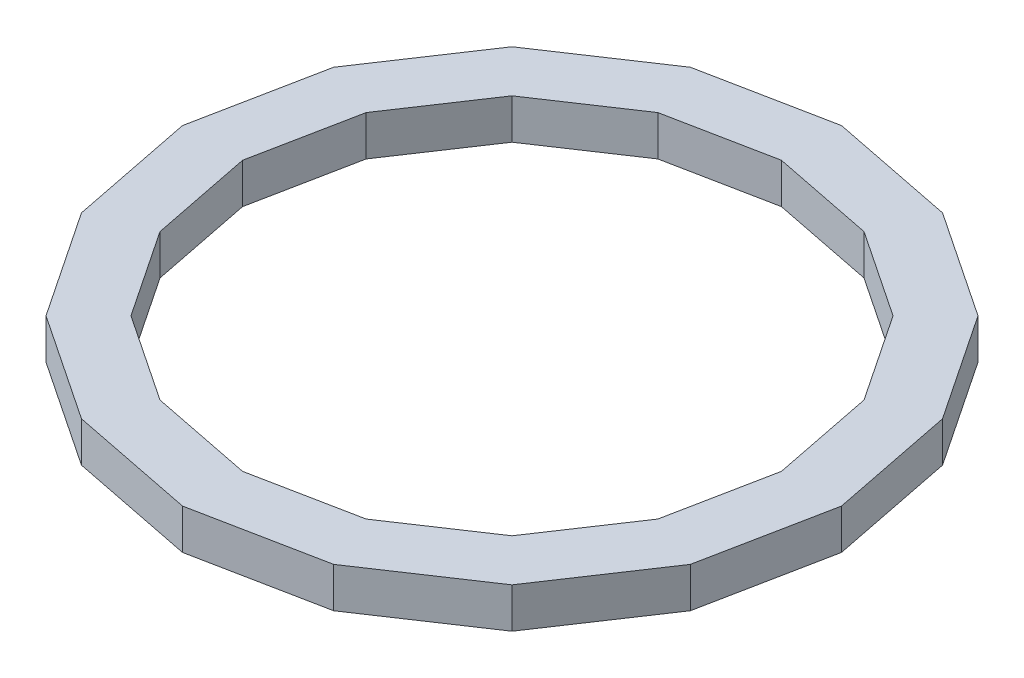
SolidWorks part; units mm, degrees
ref_plane "Front Plane" through (0, 0, 0) normal (0, 0, 1) x (1, 0, 0)
ref_plane "Top Plane" through (0, 0, 0) normal (0, 1, 0) x (1, 0, 0)
ref_plane "Right Plane" through (0, 0, 0) normal (1, 0, 0) x (0, 0, -1)
sketch "Sketch1" plane through (0, 0, 0) normal (0, 1, 0) x (1, 0, 0)
  line L1 (156.2353, 0) -> (144.3426, 59.7887)
  line L2 (144.3426, 59.7887) -> (110.4751, 110.4751)
  line L3 (110.4751, 110.4751) -> (59.7887, 144.3426)
  line L4 (59.7887, 144.3426) -> (0, 156.2353)
  line L5 (0, 156.2353) -> (-59.7887, 144.3426)
  line L6 (-59.7887, 144.3426) -> (-110.4751, 110.4751)
  line L7 (-110.4751, 110.4751) -> (-144.3426, 59.7887)
  line L8 (-144.3426, 59.7887) -> (-156.2353, 0)
  line L9 (-156.2353, 0) -> (-144.3426, -59.7887)
  line L10 (-144.3426, -59.7887) -> (-110.4751, -110.4751)
  line L11 (-110.4751, -110.4751) -> (-59.7887, -144.3426)
  line L12 (-59.7887, -144.3426) -> (0, -156.2353)
  line L13 (0, -156.2353) -> (59.7887, -144.3426)
  line L14 (59.7887, -144.3426) -> (110.4751, -110.4751)
  line L15 (110.4751, -110.4751) -> (144.3426, -59.7887)
  line L16 (144.3426, -59.7887) -> (156.2353, 0)
  line L17 (127.7479, 0) -> (118.0237, 48.887)
  line L18 (118.0237, 48.887) -> (90.3314, 90.3314)
  line L19 (90.3314, 90.3314) -> (48.887, 118.0237)
  line L20 (48.887, 118.0237) -> (0, 127.7479)
  line L21 (0, 127.7479) -> (-48.887, 118.0237)
  line L22 (-48.887, 118.0237) -> (-90.3314, 90.3314)
  line L23 (-90.3314, 90.3314) -> (-118.0237, 48.887)
  line L24 (-118.0237, 48.887) -> (-127.7479, 0)
  line L25 (-127.7479, 0) -> (-118.0237, -48.887)
  line L26 (-118.0237, -48.887) -> (-90.3314, -90.3314)
  line L27 (-90.3314, -90.3314) -> (-48.887, -118.0237)
  line L28 (-48.887, -118.0237) -> (0, -127.7479)
  line L29 (0, -127.7479) -> (48.887, -118.0237)
  line L30 (48.887, -118.0237) -> (90.3314, -90.3314)
  line L31 (90.3314, -90.3314) -> (118.0237, -48.887)
  line L32 (118.0237, -48.887) -> (127.7479, 0)
  circle A0 centre (0, 0) radius 153.2333 construction
  circle A1 centre (0, 0) radius 125.2933 construction
  dimension "D1" = 60.96
  dimension "D2" = 27.94
extrude "Boss-Extrude1" add sketch "Sketch1" along normal blind 19.05
